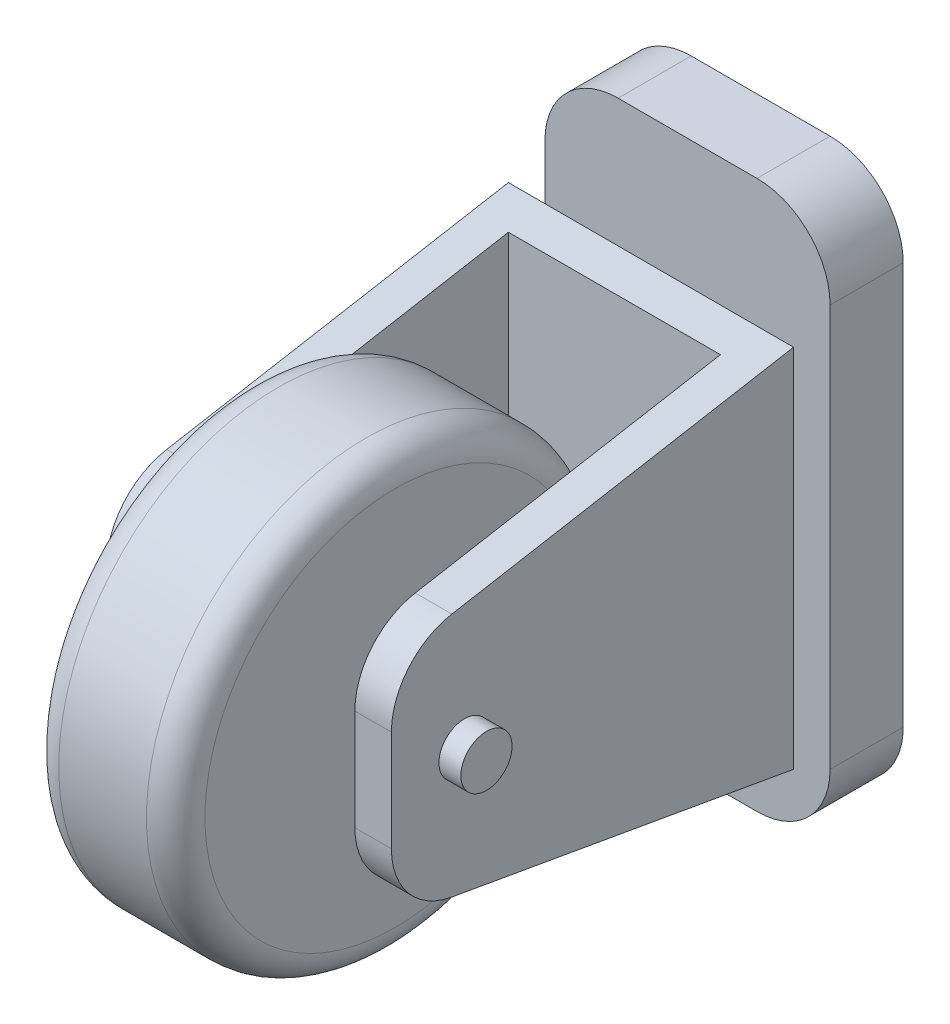
SolidWorks part; units mm, degrees
ref_plane "Front Plane" through (0, 0, 0) normal (0, 0, 1) x (1, 0, 0)
ref_plane "Top Plane" through (0, 0, 0) normal (0, 1, 0) x (1, 0, 0)
ref_plane "Right Plane" through (0, 0, 0) normal (1, 0, 0) x (0, 0, -1)
sketch "Sketch1" plane through (0, 0, 0) normal (0, 0, 1) x (1, 0, 0)
  line L1 (-315, 750) -> (-276, 750)
  line L2 (-315, 750) -> (-315, 825)
  line L3 (-315, 825) -> (-276, 825)
  line L4 (-276, 750) -> (-276, 825)
  dimension "D1" = 75
extrude "Boss-Extrude1" add sketch "Sketch1" along normal blind 10
sketch "Sketch2" plane through (0, 0, 10) normal (0, 0, 1) x (1, 0, 0)
  line L0 (-276, 787.5) -> (-315, 787.5) construction
  line L1 (-276, 750) -> (-276, 825) construction
  line L2 (-315, 825) -> (-315, 750) construction
  circle A0 centre (-295.5, 787.5) radius 10
  dimension "D1" = 20
extrude "Boss-Extrude2" add sketch "Sketch2" along normal blind 5
sketch "Sketch3" plane through (0, 0, 15) normal (0, 0, 1) x (1, 0, 0)
  line L0 (-276, 750) -> (-276, 825) construction
  line L1 (-276, 812.5) -> (-315, 812.5)
  line L2 (-276, 812.5) -> (-276, 762.5)
  line L3 (-276, 762.5) -> (-315, 762.5)
  line L4 (-315, 812.5) -> (-315, 762.5)
  line L5 (-315, 825) -> (-315, 750) construction
  line L6 (-285.5, 787.5) -> (-305.5, 787.5) construction
  circle A0 centre (-295.5, 787.5) radius 10 construction
  dimension "D1" = 50
  dimension "D2" = 25
extrude "Boss-Extrude3" add sketch "Sketch3" along normal blind 5
sketch "Sketch4" plane through (0, 0, 20) normal (0, 0, 1) x (1, 0, 0)
  line L0 (-315, 762.5) -> (-276, 762.5) construction
  line L1 (-276, 812.5) -> (-281, 812.5)
  line L2 (-276, 812.5) -> (-276, 762.5)
  line L3 (-276, 762.5) -> (-281, 762.5)
  line L4 (-281, 812.5) -> (-281, 762.5)
  line L5 (-276, 812.5) -> (-315, 812.5) construction
  line L6 (-315, 762.5) -> (-310, 762.5)
  line L7 (-315, 762.5) -> (-315, 812.5)
  line L8 (-315, 812.5) -> (-310, 812.5)
  line L9 (-310, 762.5) -> (-310, 812.5)
  dimension "D1" = 5
  dimension "D2" = 5
extrude "Boss-Extrude4" add sketch "Sketch4" along normal blind 50
sketch "Sketch5" plane through (-276, 0, 0) normal (1, 0, 0) x (0, 0, -1)
  line L0 (-15, 812.5) -> (-70, 802.802)
  line L1 (-70, 762.5) -> (-70, 812.5) construction
  line L2 (-70, 802.802) -> (-70, 812.5)
  line L3 (-70, 812.5) -> (-15, 812.5)
  line L4 (-70, 787.5) -> (-15, 787.5) construction
  line L5 (-15, 762.5) -> (-15, 812.5) construction
  line L6 (-70, 762.5) -> (-15, 762.5)
  line L7 (-70, 772.198) -> (-70, 762.5)
  line L8 (-15, 762.5) -> (-70, 772.198)
  dimension "D1" = 10
extrude "Cut-Extrude1" cut sketch "Sketch5" against normal up to surface (39 mm away) up to face at (-315, 787.5, 42.5)
fillet "Fillet1" radius 10 4 edges at (-276, 750, 5) (-315, 750, 5) (-315, 825, 5) (-276, 825, 5)
ref_plane "Plane1" through (-295.5, 0, 0) normal (1, 0, 0) x (0, 0, -1)
sketch "Sketch6" plane through (-295.5, 0, 0) normal (1, 0, 0) x (0, 0, -1)
  line L0 (-70, 772.198) -> (-70, 802.802) construction
  circle A0 centre (-60, 787.5) radius 30
  dimension "D1" = 60
  dimension "D2" = 10
extrude "Boss-Extrude5" add sketch "Sketch6" along normal mid plane 20 separate body
sketch "Sketch7" plane through (-295.5, 0, 0) normal (1, 0, 0) x (0, 0, -1)
  circle A0 centre (-60, 787.5) radius 3.5
  dimension "D1" = 7
extrude "Boss-Extrude6" add sketch "Sketch7" along normal mid plane 45
fillet "Fillet2" radius 4 2 edges at (-285.5, 787.5, 30) (-305.5, 787.5, 30)
fillet "Fillet3" radius 10 4 edges at (-278.5, 802.802, 70) (-278.5, 772.198, 70) (-312.5, 772.198, 70) (-312.5, 802.802, 70)
